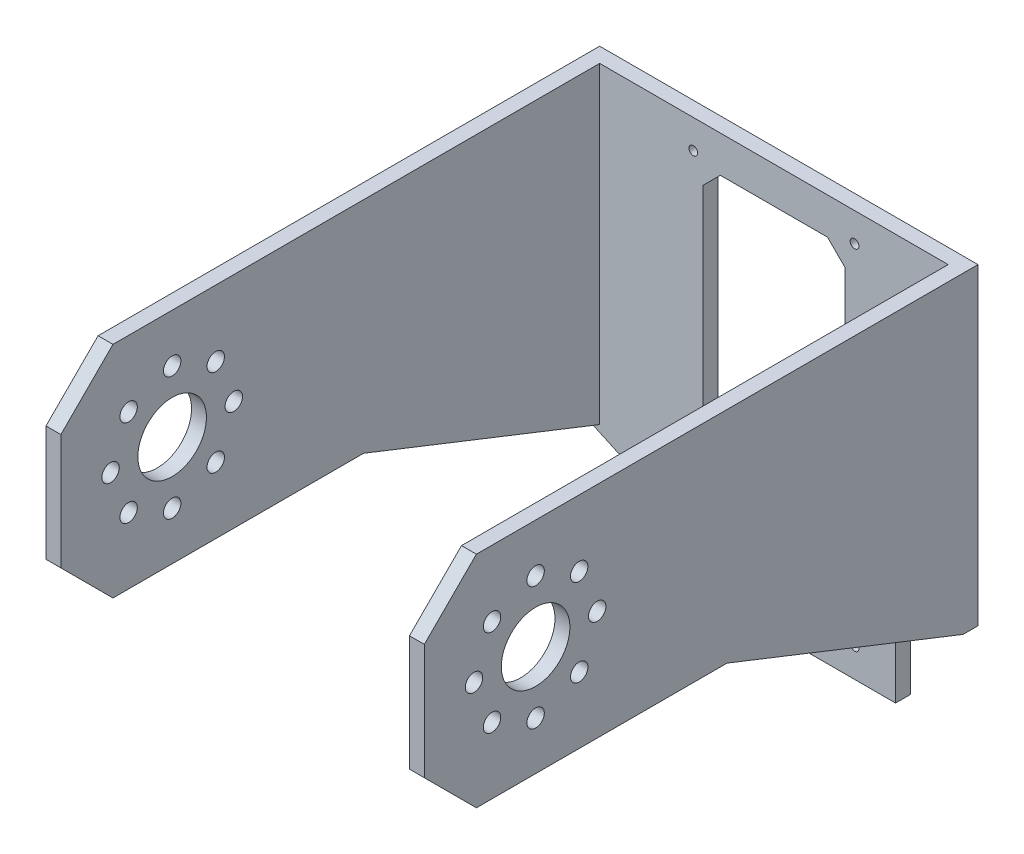
SolidWorks part; units mm, degrees
ref_plane "Front Plane" through (0, 0, 0) normal (0, 0, 1) x (1, 0, 0)
ref_plane "Top Plane" through (0, 0, 0) normal (0, 1, 0) x (1, 0, 0)
ref_plane "Right Plane" through (0, 0, 0) normal (1, 0, 0) x (0, 0, -1)
sketch "Sketch1" plane through (0, 0, 0) normal (0, 1, 0) x (1, 0, 0)
  line L0 (0, 0) -> (-21.71, 0)
  line L1 (-21.71, 0) -> (-21.71, -63.54)
  line L2 (-21.71, -63.54) -> (-20, -63.54)
  line L3 (-20, -63.54) -> (-20, -1.71)
  line L4 (-20, -1.71) -> (0, -1.71)
  line L5 (0, -1.71) -> (0, 0)
  dimension "D1" = 1.71
  dimension "D2" = 1.71
  dimension "D3" = 20
  dimension "D4" = 63.54
extrude "Boss-Extrude1" add sketch "Sketch1" along normal mid plane 25.21
sketch "Sketch2" plane through (-21.71, 0, 0) normal (-1, 0, 0) x (0, 0, 1)
  line L0 (57.565, 12.605) -> (63.54, 6.63)
  line L1 (0, 12.605) -> (63.54, 12.605) construction
  line L2 (63.54, 12.605) -> (63.54, -12.605) construction
  line L3 (63.54, 6.63) -> (63.54, -6.63) construction
  line L4 (63.54, -6.63) -> (57.565, -12.605)
  line L5 (0, -12.605) -> (63.54, -12.605) construction
  line L6 (57.565, -12.605) -> (57.565, 12.605) construction
  line L7 (0, 0) -> (63.54, 0) construction
  line L8 (57.565, 12.605) -> (63.54, 12.605)
  line L9 (63.54, 12.605) -> (63.54, 6.63)
  line L10 (57.565, -12.605) -> (63.54, -12.605)
  line L11 (63.54, -12.605) -> (63.54, -6.63)
  point P11 (63.54, 0)
  dimension "D1" = 13.26
  dimension "D2" = 45
extrude "Cut-Extrude1" cut sketch "Sketch2" against normal blind 32.2
sketch "Sketch3" plane through (-21.71, 0, 0) normal (-1, 0, 0) x (0, 0, 1)
  line L0 (50.77, 12.25) -> (50.77, 0) construction
  line L1 (55.77, -5) -> (45.77, -5) construction
  line L2 (55.77, -5) -> (55.77, 5) construction
  line L3 (55.77, 5) -> (45.77, 5) construction
  line L4 (45.77, -5) -> (45.77, 5) construction
  line L5 (55.77, -5) -> (45.77, 5) construction
  line L6 (55.77, 5) -> (45.77, -5) construction
  line L7 (50.77, 0) -> (63.54, 0) construction
  line L8 (63.54, 6.63) -> (63.54, -6.63) construction
  circle A0 centre (50.77, 0) radius 3.935
  circle A1 centre (45.77, 5) radius 1
  circle A2 centre (55.77, 5) radius 1
  circle A3 centre (55.77, -5) radius 1
  circle A4 centre (45.77, -5) radius 1
  circle A5 centre (50.77, 0) radius 7.0711 construction
  circle A6 centre (43.6989, 0) radius 1
  circle A7 centre (50.77, -7.0711) radius 1
  circle A8 centre (57.8411, 0) radius 1
  circle A9 centre (50.77, 7.0711) radius 1
  dimension "D1" = 7.87
  dimension "D3" = 2
  dimension "D2" = 45
  dimension "D4" = 10
  dimension "D5" = 12.77
extrude "Cut-Extrude2" cut sketch "Sketch3" against normal blind 32.2
mirror "Mirror1" about plane through (0, 12.605, 1.71) normal (-1, 0, 0) of "Cut-Extrude1", "Boss-Extrude1", "Cut-Extrude2"
sketch "Sketch4" plane through (0, 0, 1.71) normal (0, 0, 1) x (1, 0, 0)
  line L0 (0, 9.4948) -> (0, 0) construction
  line L1 (5, -5) -> (-5, -5) construction
  line L2 (5, -5) -> (5, 5) construction
  line L3 (5, 5) -> (-5, 5) construction
  line L4 (-5, -5) -> (-5, 5) construction
  line L5 (5, -5) -> (-5, 5) construction
  line L6 (5, 5) -> (-5, -5) construction
  line L7 (7.0711, 0) -> (0, 7.0711) construction
  line L8 (7.0711, 0) -> (0, -7.0711) construction
  line L9 (0, 7.0711) -> (-7.0711, 0) construction
  line L10 (0, -7.0711) -> (-7.0711, 0) construction
  line L11 (7.0711, 0) -> (-7.0711, 0) construction
  line L12 (0, 7.0711) -> (0, -7.0711) construction
  circle A0 centre (0, 0) radius 3.935
  circle A1 centre (-5, 5) radius 1
  circle A2 centre (5, 5) radius 1
  circle A3 centre (5, -5) radius 1
  circle A4 centre (-5, -5) radius 1
  circle A5 centre (-7.0711, 0) radius 1
  circle A6 centre (0, 7.0711) radius 1
  circle A7 centre (7.0711, 0) radius 1
  circle A8 centre (0, -7.0711) radius 1
  dimension "D1" = 7.87
  dimension "D3" = 2
  dimension "D6" = 10
  dimension "D2" = 45
  dimension "D4" = 10
  dimension "D5" = 45
extrude "Cut-Extrude3" [suppressed] cut sketch "Sketch4" against normal blind 32.2
chamfer "Chamfer1" [suppressed] distance 6 angle 45
chamfer "Chamfer2" [suppressed] distance 7 angle 45
sketch "Sketch5" plane through (0, -12.605, 0) normal (0, -1, 0) x (1, 0, 0)
  line L0 (-21.71, 28.8) -> (-20, 28.8)
  line L1 (-21.71, 0) -> (-21.71, 57.565) construction
  line L2 (-20, 57.565) -> (-20, 1.71) construction
  line L3 (-20, 28.8) -> (-20, 1.71)
  line L4 (-20, 1.71) -> (20, 1.71)
  line L5 (20, 1.71) -> (20, 28.8)
  line L6 (20, 57.565) -> (20, 1.71) construction
  line L7 (20, 28.8) -> (21.71, 28.8)
  line L8 (21.71, 0) -> (21.71, 57.565) construction
  line L9 (21.71, 28.8) -> (21.71, 0)
  line L10 (21.71, 0) -> (-21.71, 0)
  line L11 (-21.71, 0) -> (-21.71, 28.8)
  line L12 (-20, 28.8) -> (20, 28.8) construction
  dimension "D1" = 28.8
extrude "Boss-Extrude2" add sketch "Sketch5" along normal blind 21.39
sketch "Sketch6" plane through (0, 0, 0) normal (0, 0, -1) x (-1, 0, 0)
  line L0 (-21.71, 12.605) -> (-21.71, -33.995) construction
  line L1 (-21.71, -26.845) -> (-13.96, -26.845) construction
  line L2 (-21.71, -26.845) -> (-21.71, -33.995)
  line L3 (-21.71, -33.995) -> (-13.96, -33.995)
  line L4 (-13.96, -26.845) -> (-13.96, -33.995)
  line L5 (21.71, -33.995) -> (-21.71, -33.995) construction
  line L6 (-21.71, -26.845) -> (-21.71, -23.295)
  line L7 (-21.71, -23.295) -> (-13.96, -26.845)
  line L8 (0, -33.995) -> (0, 0) construction
  line L9 (21.71, -26.845) -> (13.96, -26.845) construction
  line L10 (21.71, -23.295) -> (13.96, -26.845)
  line L11 (21.71, -26.845) -> (21.71, -23.295)
  line L12 (13.96, -26.845) -> (13.96, -33.995)
  line L13 (21.71, -33.995) -> (13.96, -33.995)
  line L14 (21.71, -26.845) -> (21.71, -33.995)
  line L15 (-21.71, 12.605) -> (21.71, 12.605) construction
  line L16 (-8.15, 8.405) -> (8.15, 8.405)
  line L17 (-8.15, 8.405) -> (-8.15, -29.795)
  line L18 (-8.15, -29.795) -> (8.15, -29.795)
  line L19 (8.15, 8.405) -> (8.15, -29.795)
  line L20 (-8.15, 8.405) -> (8.15, -29.795) construction
  line L21 (-8.15, -29.795) -> (8.15, 8.405) construction
  line L23 (9.25, 9.305) -> (-9.25, 9.305) construction
  line L24 (9.25, 9.305) -> (9.25, -30.695) construction
  line L25 (9.25, -30.695) -> (-9.25, -30.695) construction
  line L26 (-9.25, 9.305) -> (-9.25, -30.695) construction
  line L27 (9.25, 9.305) -> (-9.25, -30.695) construction
  line L28 (9.25, -30.695) -> (-9.25, 9.305) construction
  circle A0 centre (-9.25, 9.305) radius 0.5
  circle A1 centre (9.25, 9.305) radius 0.5
  circle A2 centre (9.25, -30.695) radius 0.5
  circle A3 centre (-9.25, -30.695) radius 0.5
  point P17 (0, -10.695)
  point P24 (0, 12.605)
  point P25 (0, -10.695)
  dimension "D7" = 18.5
  dimension "D1" = 7.15
  dimension "D2" = 10.7
  dimension "D3" = 16.3
  dimension "D4" = 38.2
  dimension "D5" = 4.2
  dimension "D6" = 7.75
  dimension "D8" = 40
extrude "Cut-Extrude4" cut sketch "Sketch6" against normal blind 45
sketch "Sketch7" plane through (21.71, 0, 0) normal (1, 0, 0) x (0, 0, -1)
  line L0 (-28.8, -12.605) -> (-1.71, -23.295)
  line L1 (-28.8, -23.295) -> (0, -23.295) construction
  line L2 (-1.71, -23.295) -> (-1.71, -35.5938)
  line L3 (-1.71, -35.5938) -> (-28.8, -35.5938)
  line L4 (-28.8, -35.5938) -> (-28.8, -12.605)
extrude "Cut-Extrude5" cut sketch "Sketch7" against normal blind 68
chamfer "Chamfer3" distance 2 angle 45 4 edges at (8.15, 8.405, 0.855) (-8.15, 8.405, 0.855) (8.15, -29.795, 0.855) (-8.15, -29.795, 0.855)
